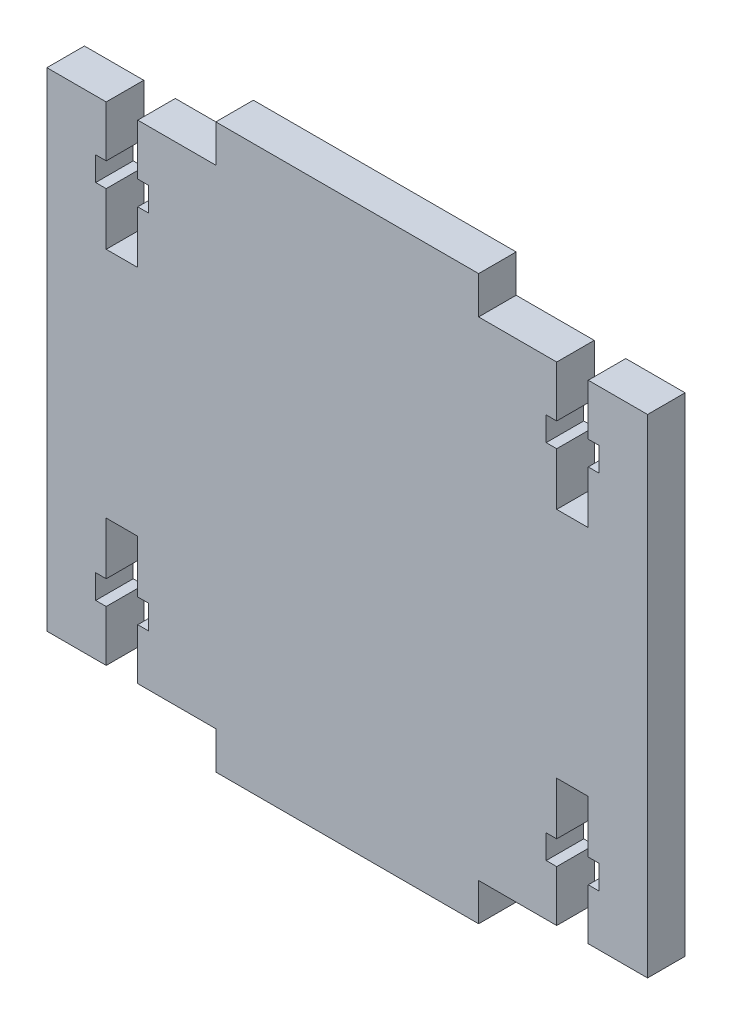
SolidWorks part; units mm, degrees
ref_plane "Front Plane" through (0, 0, 0) normal (0, 0, 1) x (1, 0, 0)
ref_plane "Top Plane" through (0, 0, 0) normal (0, 1, 0) x (1, 0, 0)
ref_plane "Right Plane" through (0, 0, 0) normal (1, 0, 0) x (0, 0, -1)
sketch "Sketch1" plane through (0, 0, 0) normal (0, 0, 1) x (1, 0, 0)
  line L0 (7.9656, 26.6306) -> (7.9656, 15.7877) construction
  line L1 (-32.0344, 26.6306) -> (47.9656, 26.6306)
  line L2 (-32.0344, 26.6306) -> (-32.0344, -38.3694)
  line L3 (-32.0344, -38.3694) -> (47.9656, -38.3694)
  line L4 (47.9656, 26.6306) -> (47.9656, -38.3694)
  line L5 (-9.5344, 26.6306) -> (25.4656, 26.6306)
  line L6 (-9.5344, 26.6306) -> (-9.5344, 31.6306)
  line L7 (-9.5344, 31.6306) -> (25.4656, 31.6306)
  line L8 (25.4656, 26.6306) -> (25.4656, 31.6306)
  line L9 (-9.5344, -38.3694) -> (25.4656, -38.3694)
  line L10 (-9.5344, -38.3694) -> (-9.5344, -43.3694)
  line L11 (-9.5344, -43.3694) -> (25.4656, -43.3694)
  line L12 (25.4656, -38.3694) -> (25.4656, -43.3694)
  line L13 (-24.1344, 26.6306) -> (-19.9344, 26.6306)
  line L14 (-24.1344, 26.6306) -> (-24.1344, 9.6306)
  line L15 (-24.1344, 9.6306) -> (-19.9344, 9.6306)
  line L16 (-19.9344, 26.6306) -> (-19.9344, 9.6306)
  line L17 (-25.5344, 19.8306) -> (-18.5344, 19.8306)
  line L18 (-25.5344, 19.8306) -> (-25.5344, 16.6306)
  line L19 (-25.5344, 16.6306) -> (-18.5344, 16.6306)
  line L20 (-18.5344, 19.8306) -> (-18.5344, 16.6306)
  line L21 (34.4656, 19.8306) -> (34.4656, 16.6306)
  line L22 (41.4656, 16.6306) -> (34.4656, 16.6306)
  line L23 (41.4656, 19.8306) -> (41.4656, 16.6306)
  line L24 (41.4656, 19.8306) -> (34.4656, 19.8306)
  line L25 (35.8656, 26.6306) -> (35.8656, 9.6306)
  line L26 (40.0656, 9.6306) -> (35.8656, 9.6306)
  line L27 (40.0656, 26.6306) -> (40.0656, 9.6306)
  line L28 (40.0656, 26.6306) -> (35.8656, 26.6306)
  line L29 (-32.0344, -5.8694) -> (-9.5344, -5.8694) construction
  line L30 (7.9656, -38.3694) -> (7.9656, -27.5265) construction
  line L31 (40.0656, -38.3694) -> (35.8656, -38.3694)
  line L32 (40.0656, -38.3694) -> (40.0656, -21.3694)
  line L33 (40.0656, -21.3694) -> (35.8656, -21.3694)
  line L34 (35.8656, -38.3694) -> (35.8656, -21.3694)
  line L35 (41.4656, -31.5694) -> (34.4656, -31.5694)
  line L36 (41.4656, -31.5694) -> (41.4656, -28.3694)
  line L37 (41.4656, -28.3694) -> (34.4656, -28.3694)
  line L38 (34.4656, -31.5694) -> (34.4656, -28.3694)
  line L39 (-18.5344, -31.5694) -> (-18.5344, -28.3694)
  line L40 (-25.5344, -28.3694) -> (-18.5344, -28.3694)
  line L41 (-25.5344, -31.5694) -> (-25.5344, -28.3694)
  line L42 (-25.5344, -31.5694) -> (-18.5344, -31.5694)
  line L43 (-19.9344, -38.3694) -> (-19.9344, -21.3694)
  line L44 (-24.1344, -21.3694) -> (-19.9344, -21.3694)
  line L45 (-24.1344, -38.3694) -> (-24.1344, -21.3694)
  line L46 (-24.1344, -38.3694) -> (-19.9344, -38.3694)
  point P12 (7.9656, -43.3694)
  point P13 (7.9656, 31.6306)
  point P22 (-22.0344, 16.6306)
  point P23 (-22.0344, 9.6306)
  dimension "D1" = 65
  dimension "D2" = 80
  dimension "D3" = 5
  dimension "D4" = 5
  dimension "D5" = 35
  dimension "D6" = 35
  dimension "D7" = 40
  dimension "D8" = 7
  dimension "D9" = 4.2
  dimension "D10" = 17
  dimension "D11" = 6.8
  dimension "D12" = 3.2
  dimension "D13" = 10
extrude "Boss-Extrude1" add sketch "Sketch1" along normal blind 5 contours L3 L45 L42 L41 L40 L44 L43 L39 L34 L35 L38 L37 L33 L32 L36 L4 L1 L27 L24 L23 L22 L26 L25 L21 L16 L17 L20 L19 L15 L14 | L1 L8 L7 L6 | L12 L3 L10 L11
